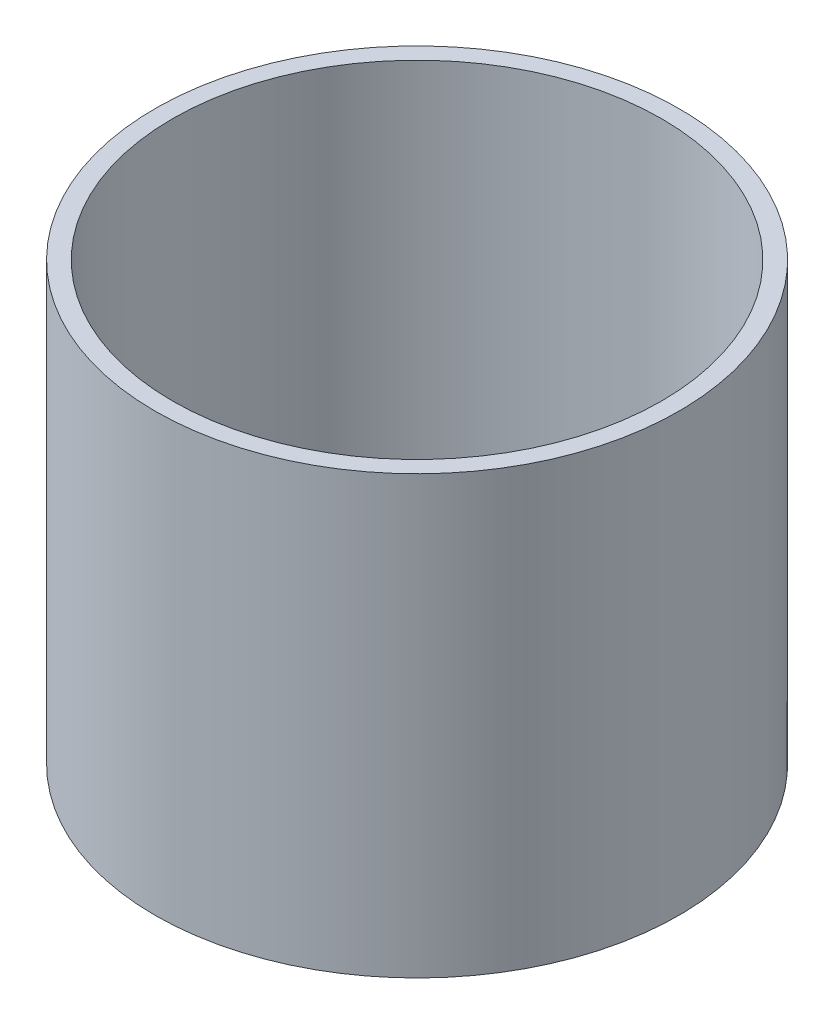
SolidWorks part; units mm, degrees
ref_plane "Front Plane" through (0, 0, 0) normal (0, 0, 1) x (1, 0, 0)
ref_plane "Top Plane" through (0, 0, 0) normal (0, 1, 0) x (1, 0, 0)
ref_plane "Right Plane" through (0, 0, 0) normal (1, 0, 0) x (0, 0, -1)
sketch "Sketch1" plane through (0, 0, 0) normal (0, 1, 0) x (1, 0, 0)
  circle A0 centre (0, 0) radius 28
  circle A1 centre (0, 0) radius 30
  dimension "D1" = 60
  dimension "D2" = 2
extrude "Boss-Extrude1" add sketch "Sketch1" along normal blind 50
